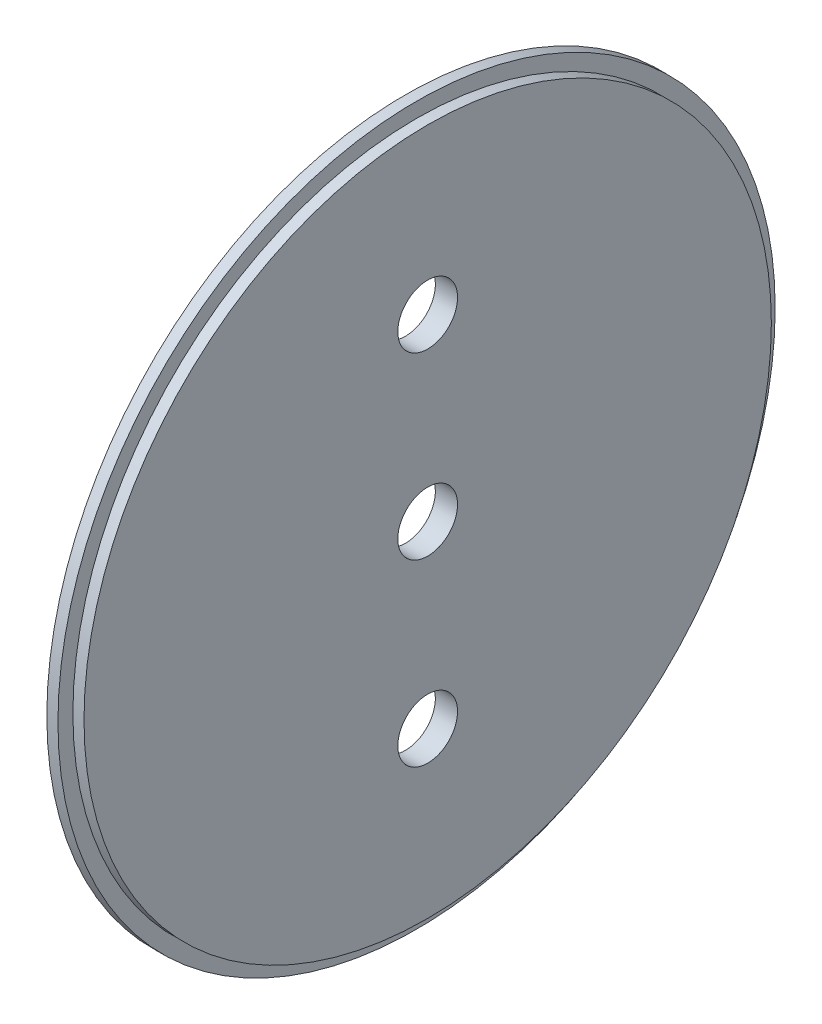
SolidWorks part; units mm, degrees
ref_plane "Front Plane" through (0, 0, 0) normal (1, 0, 0) x (0, 1, 0)
ref_plane "Top Plane" through (0, 0, 0) normal (0, 0, 1) x (0, 1, 0)
ref_plane "Right Plane" through (0, 0, 0) normal (0, 1, 0) x (-1, 0, 0)
sketch "Sketch1" plane through (0, 0, 0) normal (1, 0, 0) x (0, 1, 0)
  circle A0 centre (0, 0) radius 38.1
  dimension "D1" = 76.2
extrude "Boss-Extrude1" add sketch "Sketch1" along normal blind 1.1811
sketch "Sketch2" plane through (1.1811, 0, 0) normal (1, 0, 0) x (0, 1, 0)
  circle A0 centre (0, 0) radius 36.5125
  dimension "D1" = 73.025
extrude "Boss-Extrude2" add sketch "Sketch2" along normal blind 1.1811
sketch "Sketch3" plane through (0, 0, 0) normal (-1, 0, 0) x (0, -1, 0)
  circle A1 centre (19.05, 0) radius 3.175
  circle A2 centre (-19.05, 0) radius 3.175
  circle A3 centre (0, 0) radius 3.175
  point P2 (0, 0)
  dimension "D1" = 6.35
  dimension "D2" = 6.35
  dimension "D3" = 6.35
  dimension "D4" = 19.05
  dimension "D5" = 19.05
extrude "Cut-Extrude1" cut sketch "Sketch3" against normal through all
